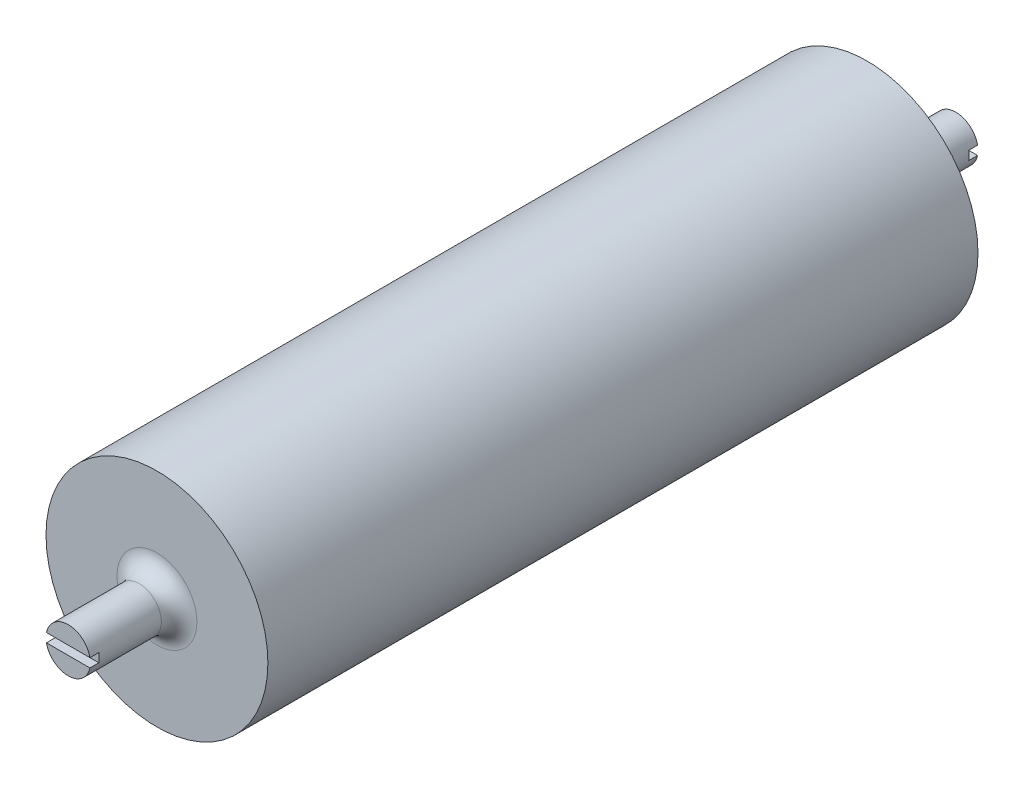
SolidWorks part; units mm, degrees
ref_plane "Plan de face" through (0, 0, 0) normal (0, 0, 1) x (1, 0, 0)
ref_plane "Plan de dessus" through (0, 0, 0) normal (0, 1, 0) x (1, 0, 0)
ref_plane "Plan de droite" through (0, 0, 0) normal (1, 0, 0) x (0, 0, -1)
sketch "Esquisse1" plane through (0, 0, 0) normal (0, 0, 1) x (1, 0, 0)
  circle A0 centre (0, 0) radius 12.5
  dimension "D1" = 25
extrude "Boss.-Extru.1" add sketch "Esquisse1" along normal blind 80
sketch "Esquisse2" plane through (0, 0, 0) normal (0, 0, 1) x (1, 0, 0)
  circle A0 centre (0, 0) radius 2.5
  dimension "D1" = 5
extrude "Boss.-Extru.2" add sketch "Esquisse2" against normal blind 10 and the other way blind 90
fillet "Congé1" radius 2 1 edges at (2.5, 0, 80)
fillet "Congé2" radius 2 1 edges at (2.5, 0, 0)
sketch "Esquisse3" plane through (0, 0, 90) normal (0, 0, 1) x (1, 0, 0)
  circle A0 centre (0, 0) radius 0.5
  point P2 (0, 0)
  dimension "D1" = 1
extrude "Enlèv. mat.-Extru.1" cut sketch "Esquisse3" against normal blind 90 from offset 5 offset against normal yes
sketch "Esquisse4" plane through (0, 0, -10) normal (0, 0, -1) x (-1, 0, 0)
  line L0 (-2.5, 0) -> (2.5, 0) construction
  line L1 (-2.4495, -0.5) -> (2.4495, -0.5)
  line L2 (-2.4495, 0.5) -> (2.4495, 0.5)
  arc A0 (2.4495, -0.5) -> (2.4495, 0.5) centre (0, 0) ccw
  circle A1 centre (0, 0) radius 2.5
  arc A2 (-2.4495, 0.5) -> (-2.4495, -0.5) centre (0, 0) ccw
  point P5 (0, 0)
  dimension "D2" = 0.5
  dimension "D1" = 0
extrude "Enlèv. mat.-Extru.2" cut sketch "Esquisse4" against normal blind 1
sketch "Esquisse5" plane through (0, 0, 90) normal (0, 0, 1) x (1, 0, 0)
  line L0 (-2.5, 0) -> (2.5, 0) construction
  line L1 (-2.4495, -0.5) -> (2.4495, -0.5)
  line L2 (-2.4495, 0.5) -> (2.4495, 0.5)
  arc A0 (2.4495, -0.5) -> (2.4495, 0.5) centre (0, 0) ccw
  circle A1 centre (0, 0) radius 2.5
  arc A2 (-2.4495, 0.5) -> (-2.4495, -0.5) centre (0, 0) ccw
  point P5 (0, 0)
  dimension "D2" = 0.5
  dimension "D1" = 0
extrude "Enlèv. mat.-Extru.3" cut sketch "Esquisse5" against normal blind 1
